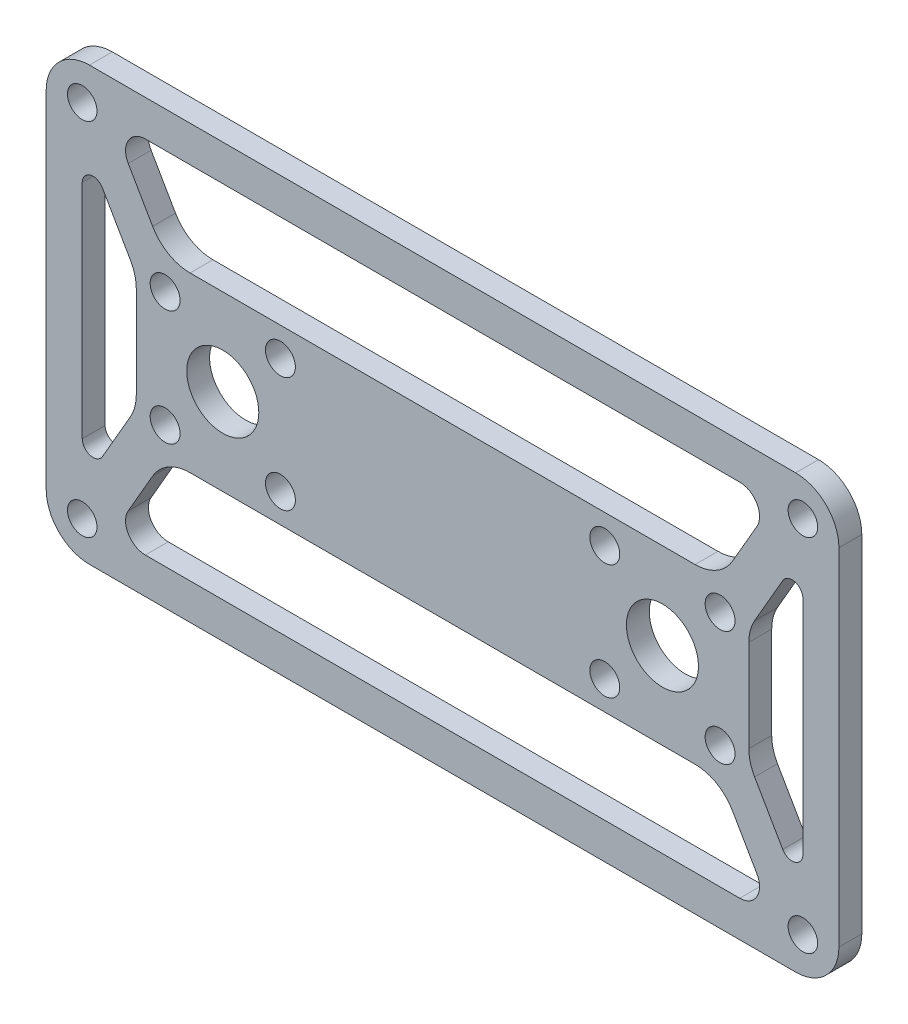
SolidWorks part; units mm, degrees
ref_plane "Front Plane" through (0, 0, 0) normal (0, 0, 1) x (1, 0, 0)
ref_plane "Top Plane" through (0, 0, 0) normal (0, 1, 0) x (1, 0, 0)
ref_plane "Right Plane" through (0, 0, 0) normal (1, 0, 0) x (0, 0, -1)
ref_plane "Plane1" through (0, 0, 0) normal (0, 0, -1) x (-1, 0, 0)
sketch "Sketch1" plane through (0, 0, 0) normal (0, 0, -1) x (-1, 0, 0)
  line L0 (-42.5, 6.3933) -> (-42.5, -6.3933)
  line L1 (-43.3029, -9.3917) -> (-47.2007, -16.1479)
  line L2 (-50, -15.3983) -> (-50, 15.3983)
  line L3 (-47.2007, 16.1479) -> (-43.3029, 9.3917)
  line L4 (-35.0346, -12) -> (35.0346, -12)
  line L5 (40.2317, -15.0017) -> (43.6206, -20.8758)
  line L6 (41.2386, -25) -> (-41.2386, -25)
  line L7 (-43.6206, -20.8758) -> (-40.2317, -15.0017)
  line L8 (42.5, -6.3933) -> (42.5, 6.3933)
  line L9 (43.3029, 9.3917) -> (47.2007, 16.1479)
  line L10 (50, 15.3983) -> (50, -15.3983)
  line L11 (47.2007, -16.1479) -> (43.3029, -9.3917)
  line L12 (35.0346, 12) -> (-35.0346, 12)
  line L13 (-40.2317, 15.0017) -> (-43.6206, 20.8758)
  line L14 (-41.2386, 25) -> (41.2386, 25)
  line L15 (43.6206, 20.8758) -> (40.2317, 15.0017)
  line L16 (49, 30) -> (-49, 30)
  line L17 (-55, 24) -> (-55, -24)
  line L18 (-49, -30) -> (49, -30)
  line L19 (55, -24) -> (55, 24)
  line L21 (-22.51, -8) -> (-38.51, -8) construction
  line L22 (-22.51, -8) -> (-22.51, 8) construction
  line L23 (-22.51, 8) -> (-38.51, 8) construction
  line L24 (-38.51, -8) -> (-38.51, 8) construction
  line L25 (-30.51, 8) -> (-30.51, -8) construction
  line L26 (-22.51, 0) -> (-38.51, 0) construction
  arc A0 (-42.5, -6.3933) -> (-43.3029, -9.3917) centre (-48.5, -6.3933) cw
  arc A1 (-47.2007, -16.1479) -> (-50, -15.3983) centre (-48.5, -15.3983) cw
  arc A2 (-50, 15.3983) -> (-47.2007, 16.1479) centre (-48.5, 15.3983) cw
  arc A3 (-43.3029, 9.3917) -> (-42.5, 6.3933) centre (-48.5, 6.3933) cw
  arc A4 (35.0346, -12) -> (40.2317, -15.0017) centre (35.0346, -18) cw
  arc A5 (43.6206, -20.8758) -> (41.2386, -25) centre (41.2386, -22.25) cw
  arc A6 (-41.2386, -25) -> (-43.6206, -20.8758) centre (-41.2386, -22.25) cw
  arc A7 (-40.2317, -15.0017) -> (-35.0346, -12) centre (-35.0346, -18) cw
  circle A8 centre (-30.51, 0) radius 5
  circle A9 centre (30.5, 0) radius 5
  circle A10 centre (-22.51, -8) radius 2.075
  circle A11 centre (-38.51, -8) radius 2.075
  circle A12 centre (-38.51, 8) radius 2.075
  circle A13 centre (-22.51, 8) radius 2.075
  circle A14 centre (38.5, -8) radius 2.075
  circle A15 centre (22.5, -8) radius 2.075
  circle A16 centre (22.5, 8) radius 2.075
  circle A17 centre (38.5, 8) radius 2.075
  circle A18 centre (50, -25) radius 2.05
  circle A19 centre (-50, -25) radius 2.05
  circle A20 centre (-50, 25) radius 2.05
  circle A21 centre (50, 25) radius 2.05
  arc A22 (42.5, 6.3933) -> (43.3029, 9.3917) centre (48.5, 6.3933) cw
  arc A23 (47.2007, 16.1479) -> (50, 15.3983) centre (48.5, 15.3983) cw
  arc A24 (50, -15.3983) -> (47.2007, -16.1479) centre (48.5, -15.3983) cw
  arc A25 (43.3029, -9.3917) -> (42.5, -6.3933) centre (48.5, -6.3933) cw
  arc A26 (-35.0346, 12) -> (-40.2317, 15.0017) centre (-35.0346, 18) cw
  arc A27 (-43.6206, 20.8758) -> (-41.2386, 25) centre (-41.2386, 22.25) cw
  arc A28 (41.2386, 25) -> (43.6206, 20.8758) centre (41.2386, 22.25) cw
  arc A29 (40.2317, 15.0017) -> (35.0346, 12) centre (35.0346, 18) cw
  arc A30 (-49, 30) -> (-55, 24) centre (-49, 24) ccw
  arc A31 (-55, -24) -> (-49, -30) centre (-49, -24) ccw
  arc A32 (49, -30) -> (55, -24) centre (49, -24) ccw
  arc A33 (55, 24) -> (49, 30) centre (49, 24) ccw
  dimension "D1" = 16
  dimension "D2" = 16
extrude "Boss-Extrude1" add sketch "Sketch1" against normal blind 3.175
